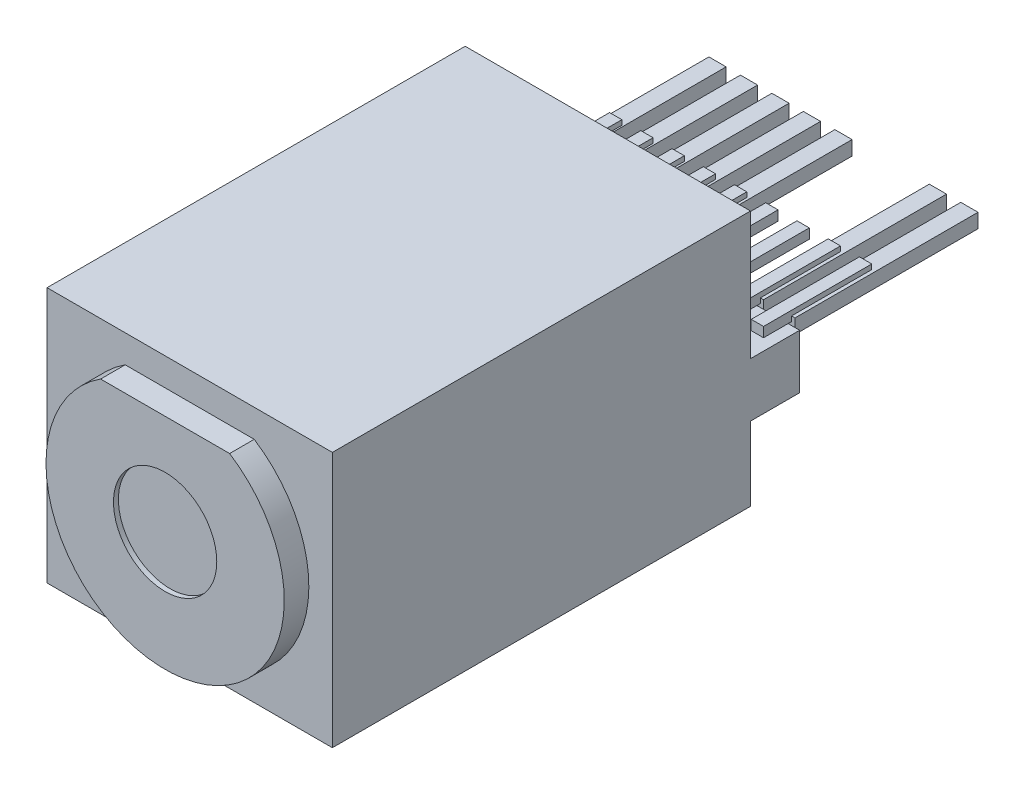
SolidWorks part; units mm, degrees
ref_plane "Front Plane" through (0, 0, 0) normal (0, 0, 1) x (1, 0, 0)
ref_plane "Top Plane" through (0, 0, 0) normal (0, 1, 0) x (1, 0, 0)
ref_plane "Right Plane" through (0, 0, 0) normal (1, 0, 0) x (0, 0, -1)
sketch "Sketch1" plane through (0, 0, 0) normal (0, 0, 1) x (1, 0, 0)
  line L1 (0, 0) -> (5.8, 0)
  line L2 (0, 0) -> (0, 5.2)
  line L3 (0, 5.2) -> (5.8, 5.2)
  line L4 (5.8, 0) -> (5.8, 5.2)
  dimension "D1" = 5.8
  dimension "D2" = 5.2
extrude "Boss-Extrude1" add sketch "Sketch1" against normal blind 8.5
sketch "Sketch3" plane through (0, 0, 0) normal (0, 0, 1) x (1, 0, 0)
  line L0 (1.5885, 4.6358) -> (4.2115, 4.6358)
  line L1 (0, 0) -> (5.8, 0) construction
  line L2 (0, 5.2) -> (0, 0) construction
  arc A0 (1.5885, 4.6358) -> (4.2115, 4.6358) centre (2.9, 2.6) ccw
  dimension "D1" = 2.6
  dimension "D2" = 2.9
extrude "Boss-Extrude2" add sketch "Sketch3" along normal blind 0.5
sketch "Sketch4" plane through (0, 0, -8.5) normal (0, 0, -1) x (-1, 0, 0)
  line L0 (-5.8, 0) -> (-5.8, 5.2) construction
  line L1 (-5.8, 2.6) -> (0, 2.6)
  line L2 (-5.8, 2.6) -> (-5.8, 1.5)
  line L3 (-5.8, 1.5) -> (0, 1.5)
  line L4 (0, 2.6) -> (0, 1.5)
  line L5 (0, 5.2) -> (0, 0) construction
  line L6 (0, 0) -> (-5.8, 0) construction
  dimension "D1" = 2.6
  dimension "D2" = 1.1
extrude "Boss-Extrude3" add sketch "Sketch4" along normal blind 1
sketch "Sketch10" plane through (0, 0, -8.5) normal (0, 0, -1) x (-1, 0, 0)
  line L0 (-3.025, 2.8) -> (-3.025, 2.6)
  line L1 (-3.025, 2.8) -> (-2.775, 2.8)
  line L2 (-3.025, 2.6) -> (-2.775, 2.6)
  line L3 (-2.775, 2.8) -> (-2.775, 2.6)
  line L4 (-3.025, 2.8) -> (-2.775, 2.6) construction
  line L5 (-3.025, 2.6) -> (-2.775, 2.8) construction
  line L7 (-2.9, 2.7) -> (-2.9, 2.6) construction
  line L8 (0, 2.6) -> (-5.8, 2.6) construction
  point P1 (-2.9, 2.7)
  dimension "D1" = 0.25
  dimension "D2" = 0.2
extrude "Boss-Extrude6" add sketch "Sketch10" along normal blind 2.2 from offset 0.5
sketch "Sketch11" plane through (0, 0, -9.5) normal (0, 0, -1) x (-1, 0, 0)
  line L0 (-2.725, 2.409) -> (-2.725, 2.7)
  line L1 (-2.725, 2.409) -> (-3.075, 2.409)
  line L2 (-2.725, 2.7) -> (-3.075, 2.7)
  line L3 (-3.075, 2.409) -> (-3.075, 2.7)
  line L4 (-2.725, 2.409) -> (-3.075, 2.7) construction
  line L5 (-2.725, 2.7) -> (-3.075, 2.409) construction
  line L7 (-2.9, 2.5545) -> (-2.9, 2.7) construction
  line L10 (-2.775, 2.8) -> (-3.025, 2.8) construction
  point P1 (-2.9, 2.5545)
  dimension "D1" = 0.291
  dimension "D2" = 0.35
  dimension "D3" = 0.1
extrude "Boss-Extrude7" add sketch "Sketch11" along normal blind 3.72 from offset 0.07
pattern_linear "LPattern3" count 5 spacing 0.635 along (-1, 0, 0) count 5 spacing 0.635 along (1, 0, 0) of "Boss-Extrude6"
pattern_linear "LPattern4" count 5 spacing 0.64 along (-1, 0, 0) count 5 spacing 0.64 along (1, 0, 0) of "Boss-Extrude7"
sketch "Sketch12" plane through (0, 0, 0.5) normal (0, 0, 1) x (1, 0, 0)
sketch "Sketch13" plane through (0, 0, 0.5) normal (0, 0, 1) x (1, 0, 0)
  circle A0 centre (2.9, 2.6) radius 1.05
  arc A1 (1.5885, 4.6358) -> (4.2115, 4.6358) centre (2.9, 2.6) ccw construction
extrude "Cut-Extrude1" cut sketch "Sketch13" against normal blind 0.1
